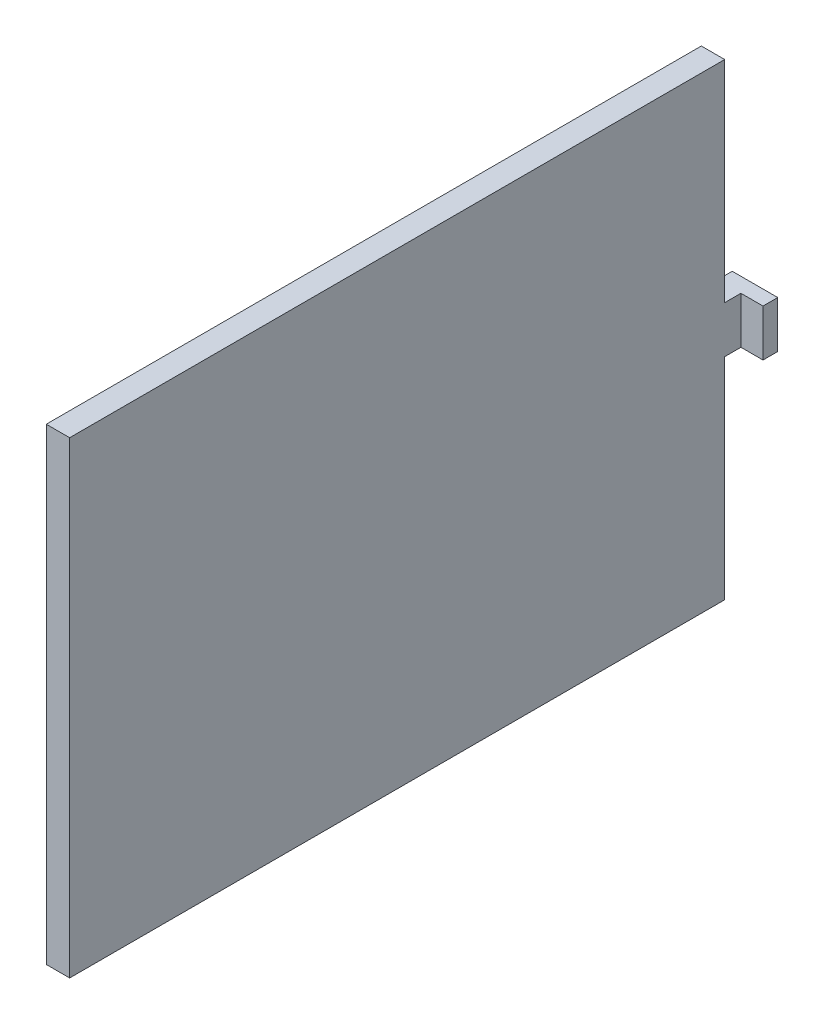
SolidWorks part; units mm, degrees
ref_plane "Front Plane" through (0, 0, 0) normal (0, 0, 1) x (1, 0, 0)
ref_plane "Top Plane" through (0, 0, 0) normal (0, 1, 0) x (1, 0, 0)
ref_plane "Right Plane" through (0, 0, 0) normal (1, 0, 0) x (0, 0, -1)
sketch "Sketch1" plane through (0, 0, 0) normal (0, 0, 1) x (1, 0, 0)
  line L0 (0, 31.75) -> (0, -31.75) construction
  line L1 (-1.5875, -31.75) -> (1.5875, -31.75)
  line L2 (-1.5875, -31.75) -> (-1.5875, 31.75)
  line L3 (-1.5875, 31.75) -> (1.5875, 31.75)
  line L4 (1.5875, -31.75) -> (1.5875, 31.75)
  line L5 (-1.5875, 0) -> (1.5875, 0) construction
  point P9 (0, 0)
  dimension "D1" = 3.175
  dimension "D2" = 63.5
extrude "Boss-Extrude1" add sketch "Sketch1" along normal blind 88.9
sketch "Sketch2" plane through (0, 0, 0) normal (0, 1, 0) x (1, 0, 0)
  line L0 (1.5875, 0) -> (1.5875, 2.2)
  line L1 (1.5875, 2.2) -> (4.5847, 2.2)
  line L2 (4.5847, 2.2) -> (4.5847, 4.2)
  line L3 (4.5847, 4.2) -> (-1.5875, 4.2)
  line L4 (-1.5875, 4.2) -> (-1.5875, 0)
  line L5 (1.5875, 0) -> (-1.5875, 0) construction
  line L6 (-1.5875, 0) -> (1.5875, 0)
  point P3 (-2.1865, 4.2)
  point P10 (-1.5875, 0)
  dimension "D1" = 2.2
  dimension "D2" = 2
  dimension "D3" = 2.9972
extrude "Boss-Extrude2" add sketch "Sketch2" along normal mid plane 6.35
